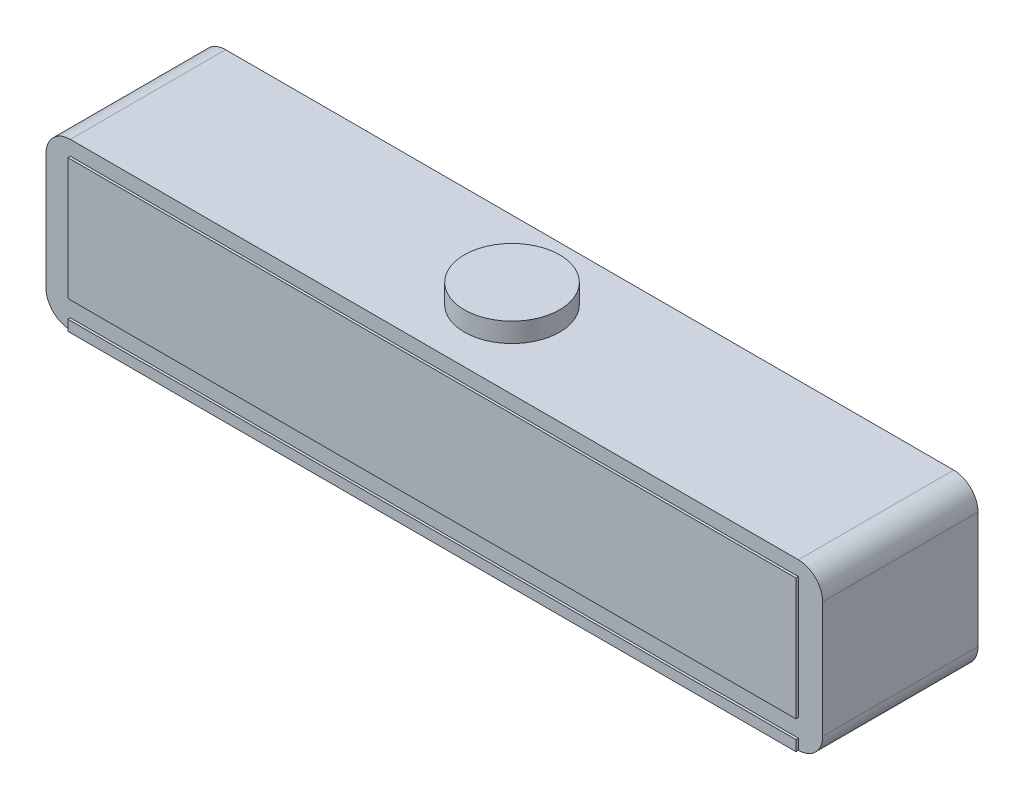
SolidWorks part; units mm, degrees
ref_plane "前视基准面" through (0, 0, 0) normal (0, 0, 1) x (1, 0, 0)
ref_plane "上视基准面" through (0, 0, 0) normal (0, 1, 0) x (1, 0, 0)
ref_plane "右视基准面" through (0, 0, 0) normal (1, 0, 0) x (0, 0, -1)
sketch "草图1" plane through (0, 0, 0) normal (0, 1, 0) x (1, 0, 0)
  line L1 (-133.578, -1.6881) -> (186.422, -1.6881)
  line L2 (-133.578, -1.6881) -> (-133.578, -65.6881)
  line L3 (-133.578, -65.6881) -> (186.422, -65.6881)
  line L4 (186.422, -1.6881) -> (186.422, -65.6881)
  dimension "D1" = 320
  dimension "D2" = 64
extrude "凸台-拉伸1" add sketch "草图1" along normal blind 68
fillet "圆角1" radius 10 4 edges at (186.422, 0, 33.6881) (186.422, 68, 33.6881) (-133.578, 0, 33.6881) (-133.578, 68, 33.6881)
sketch "草图2" plane through (0, 68, 0) normal (0, 1, 0) x (1, 0, 0)
  line L0 (-123.578, -33.6881) -> (176.422, -33.6881) construction
  line L1 (-123.578, -1.6881) -> (-123.578, -65.6881) construction
  line L2 (176.422, -65.6881) -> (176.422, -1.6881) construction
  line L3 (26.422, -1.6881) -> (26.422, -65.6881) construction
  line L4 (176.422, -1.6881) -> (-123.578, -1.6881) construction
  line L5 (-123.578, -65.6881) -> (176.422, -65.6881) construction
  circle A0 centre (26.422, -33.6881) radius 19.6249
extrude "凸台-拉伸2" add sketch "草图2" along normal blind 8
sketch "草图3" plane through (0, 0, 65.6881) normal (0, 0, 1) x (1, 0, 0)
  line L1 (-123.578, 62) -> (176.422, 62)
  line L2 (-123.578, 62) -> (-123.578, 11.712)
  line L3 (-123.578, 11.712) -> (176.422, 11.712)
  line L4 (176.422, 62) -> (176.422, 11.712)
  line L5 (-133.578, 58) -> (-133.578, 10) construction
  line L6 (-123.578, 68) -> (176.422, 68) construction
  line L7 (-123.578, 0) -> (176.422, 0) construction
  line L8 (-123.578, 4.3447) -> (176.422, 4.3447)
  line L9 (-123.578, 4.3447) -> (-123.578, 0)
  line L10 (-123.578, 0) -> (176.422, 0)
  line L11 (176.422, 4.3447) -> (176.422, 0)
  dimension "D1" = 300
  dimension "D2" = 10
  dimension "D3" = 6
extrude "凸台-拉伸3" add sketch "草图3" along normal blind 1
